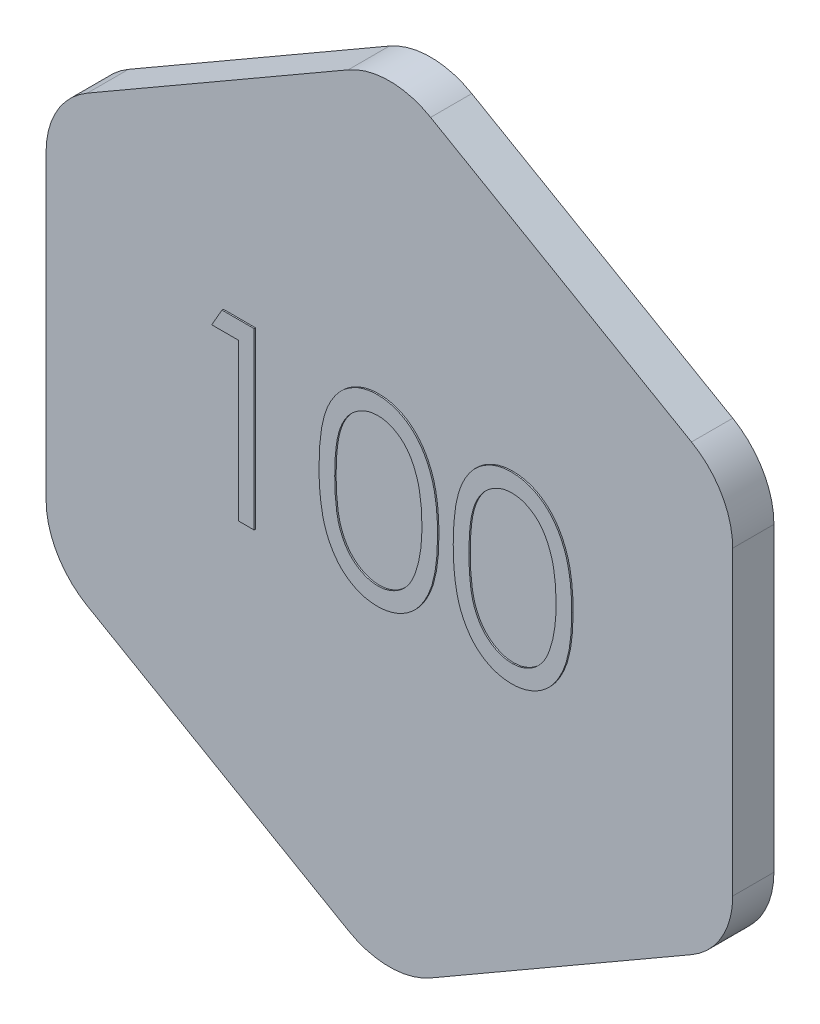
SolidWorks part; units mm, degrees
ref_plane "Front Plane" through (0, 0, 0) normal (1, 0, 0) x (0, 1, 0)
ref_plane "Top Plane" through (0, 0, 0) normal (0, 0, 1) x (0, 1, 0)
ref_plane "Right Plane" through (0, 0, 0) normal (0, 1, 0) x (-1, 0, 0)
sketch "Sketch1" plane through (0, 0, 0) normal (0, 0, 1) x (0, 1, 0)
  line L0 (0, 0) -> (-50.3722, 0) construction
  line L1 (16.1658, -22) -> (27.1355, -3)
  line L2 (27.1355, 3) -> (16.1658, 22)
  line L3 (10.9697, 25) -> (-10.9697, 25)
  line L4 (-16.1658, 22) -> (-27.1355, 3)
  line L5 (-27.1355, -3) -> (-16.1658, -22)
  line L6 (-10.9697, -25) -> (10.9697, -25)
  circle A0 centre (0, 0) radius 25 construction
  arc A1 (-10.9697, 25) -> (-16.1658, 22) centre (-10.9697, 19) ccw
  arc A2 (-27.1355, -3) -> (-27.1355, 3) centre (-21.9393, 0) cw
  arc A3 (-10.9697, -25) -> (-16.1658, -22) centre (-10.9697, -19) cw
  arc A4 (10.9697, -25) -> (16.1658, -22) centre (10.9697, -19) ccw
  arc A5 (27.1355, -3) -> (27.1355, 3) centre (21.9393, 0) ccw
  arc A6 (16.1658, 22) -> (10.9697, 25) centre (10.9697, 19) ccw
  dimension "D1" = 50
  dimension "D2" = 6
  dimension "D3" = 6
extrude "Boss-Extrude2" add sketch "Sketch1" along normal blind 3
sketch "Sketch2" plane through (0, 0, 3) normal (0, 0, 1) x (1, 0, 0)
  text T0 "100" font "Century Gothic" height in points 48
extrude "Boss-Extrude3" add sketch "Sketch2" along normal blind 0.1
